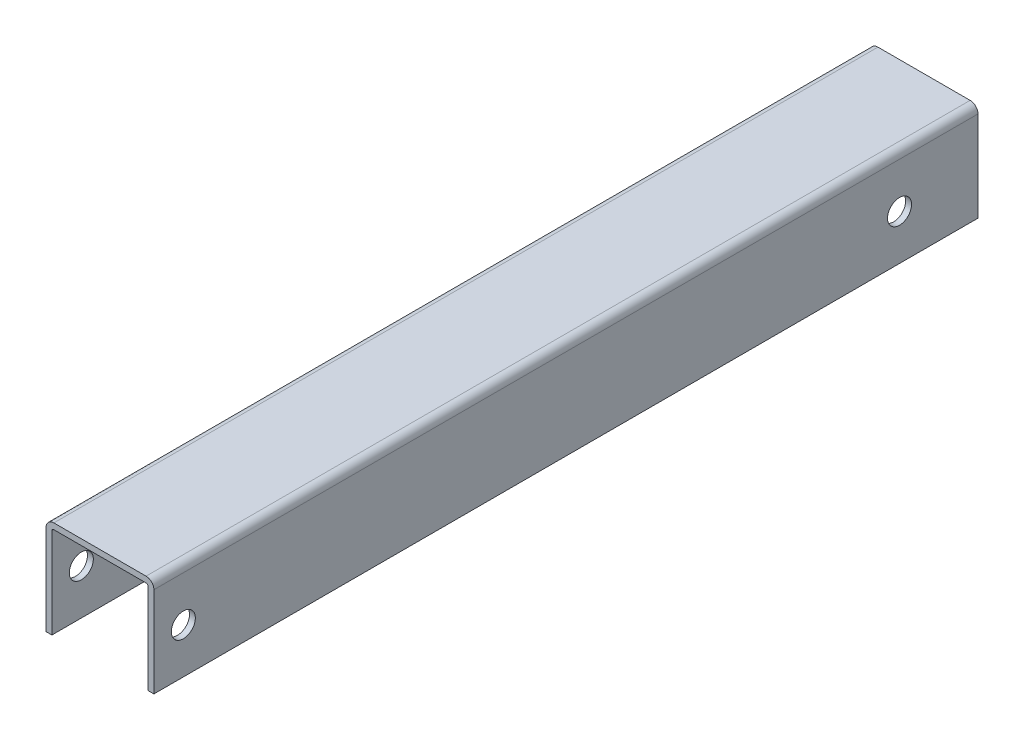
SolidWorks part; units mm, degrees
ref_plane "Ön Düzlem" through (0, 0, 0) normal (0, 0, 1) x (1, 0, 0)
ref_plane "Üst Düzlem" through (0, 0, 0) normal (0, 1, 0) x (1, 0, 0)
ref_plane "Sağ Düzlem" through (0, 0, 0) normal (1, 0, 0) x (0, 0, -1)
sketch "Çizim1" plane through (0, 0, 0) normal (0, 0, 1) x (1, 0, 0)
  line L0 (-25.4431, 22.8736) -> (29.5569, 22.8736)
  line L1 (-25.4431, 22.8736) -> (-25.4431, -27.1264)
  line L2 (29.5569, 22.8736) -> (29.5569, -27.1264)
  dimension "D1" = 55
  dimension "D2" = 50
  dimension "D3" = 50
extrude "Ekstrüzyon-İnce6" add sketch "Çizim1" along normal blind 420 thin
hole_wizard "M12 Helisarmal için Zıvana matkabı2" positions "Çizim5" profile "Çizim6" size "M12x1.5" standard "ANSI Metrik" slot yes end condition through all
sketch "Çizim5" plane through (-25.4431, 0, 0) normal (-1, 0, 0) x (0, 0, 1)
  line L0 (0, -27.1264) -> (0, 18.8736) construction
  line L3 (420, 18.8736) -> (0, 18.8736) construction
  point P0 (40, -4.1264)
  point P9 (16.3729, -29.4439)
  point P16 (39.5024, 18.8736)
  dimension "D1" = 40
  dimension "D2" = 23
sketch "Çizim6" plane through (-25.4431, -4.1264, 40) normal (0, 1, 0) x (0, 0, 1)
  line L0 (0, 0) -> (0, 55)
  line L1 (0, 55) -> (6.125, 55)
  line L2 (6.125, 55) -> (6.125, 0)
  line L5 (6.125, 0) -> (0, 0)
  line L11 (0, -6.35) -> (0, 107.95) construction
  dimension "Thru Hole Dia." = 12.25
  dimension "Thru Hole Depth" = 55
hole_wizard "M12 Helisarmal için Zıvana matkabı1" positions "Çizim7" profile "Çizim8" size "M12x1.5" standard "ANSI Metrik" slot yes end condition through all
sketch "Çizim7" plane through (-25.4431, 0, 0) normal (-1, 0, 0) x (0, 0, 1)
  line L0 (420, -27.1264) -> (420, 18.8736) construction
  line L1 (420, 18.8736) -> (0, 18.8736) construction
  point P0 (405, -4.1264)
  point P5 (420, -4.1264)
  dimension "D1" = 15
  dimension "D2" = 23
sketch "Çizim8" plane through (-25.4431, -4.1264, 405) normal (0, 1, 0) x (0, 0, 1)
  line L0 (0, 0) -> (0, 55)
  line L1 (0, 55) -> (6.125, 55)
  line L2 (6.125, 55) -> (6.125, 0)
  line L5 (6.125, 0) -> (0, 0)
  line L11 (0, -6.35) -> (0, 107.95) construction
  dimension "Thru Hole Dia." = 12.25
  dimension "Thru Hole Depth" = 55
